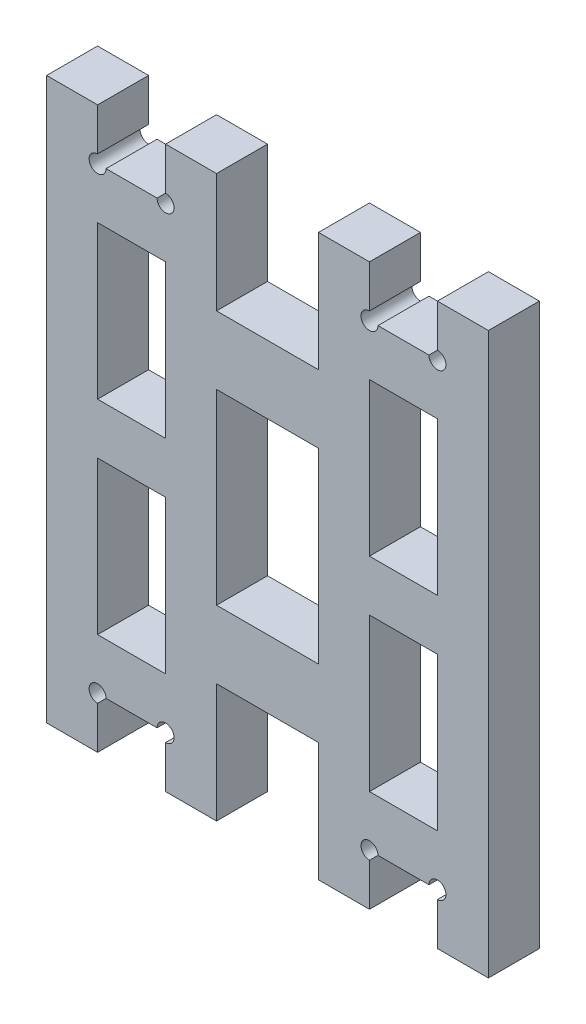
SolidWorks part; units mm, degrees
ref_plane "前视基准面" through (0, 0, 0) normal (0, 0, 1) x (1, 0, 0)
ref_plane "上视基准面" through (0, 0, 0) normal (0, 1, 0) x (1, 0, 0)
ref_plane "右视基准面" through (0, 0, 0) normal (1, 0, 0) x (0, 0, -1)
sketch "草图1" plane through (0, 0, 0) normal (0, 0, 1) x (1, 0, 0)
  line L0 (10, 26) -> (10, 33)
  line L1 (16, 26) -> (10, 26)
  line L2 (16, 22) -> (10, 22)
  line L3 (16, 33) -> (16, 26)
  line L4 (19, 33) -> (16, 33)
  line L5 (19, 30.5) -> (19, 33)
  line L6 (22.5, 30) -> (19.5, 30)
  line L7 (23, 33) -> (23, 30.5)
  line L8 (26, 33) -> (23, 33)
  line L9 (26, 0) -> (26, 33)
  line L10 (23, 0) -> (26, 0)
  line L11 (23, 2.5) -> (23, 0)
  line L12 (19.5, 3) -> (22.5, 3)
  line L13 (19, 0) -> (19, 2.5)
  line L14 (16, 0) -> (19, 0)
  line L15 (16, 7) -> (16, 0)
  line L16 (10, 0) -> (10, 7)
  line L17 (7, 0) -> (10, 0)
  line L18 (7, 2.5) -> (7, 0)
  line L19 (3.5, 3) -> (6.5, 3)
  line L20 (3, 0) -> (3, 2.5)
  line L21 (0, 0) -> (3, 0)
  line L22 (0, 33) -> (0, 0)
  line L23 (3, 33) -> (0, 33)
  line L24 (3, 30.5) -> (3, 33)
  line L25 (6.5, 30) -> (3.5, 30)
  line L26 (7, 33) -> (7, 30.5)
  line L27 (10, 33) -> (7, 33)
  line L28 (16, 7) -> (10, 7)
  line L29 (7, 18) -> (7, 27)
  line L30 (10, 11) -> (10, 22)
  line L31 (7, 27) -> (3, 27)
  line L32 (3, 27) -> (3, 18)
  line L33 (3, 18) -> (7, 18)
  line L34 (7, 6) -> (7, 15)
  line L35 (7, 15) -> (3, 15)
  line L36 (3, 15) -> (3, 6)
  line L37 (3, 6) -> (7, 6)
  line L38 (19, 15) -> (19, 6)
  line L39 (19, 6) -> (23, 6)
  line L40 (23, 6) -> (23, 15)
  line L41 (23, 15) -> (19, 15)
  line L42 (23, 18) -> (23, 27)
  line L43 (23, 27) -> (19, 27)
  line L44 (19, 27) -> (19, 18)
  line L45 (16, 22) -> (16, 11)
  line L46 (19, 18) -> (23, 18)
  line L47 (16, 11) -> (10, 11)
  arc A0 (19, 30.5) -> (19.5, 30) centre (19, 30) ccw
  arc A1 (22.5, 30) -> (23, 30.5) centre (23, 30) ccw
  arc A2 (23, 2.5) -> (22.5, 3) centre (23, 3) ccw
  arc A3 (19.5, 3) -> (19, 2.5) centre (19, 3) ccw
  arc A4 (7, 2.5) -> (6.5, 3) centre (7, 3) ccw
  arc A5 (3.5, 3) -> (3, 2.5) centre (3, 3) ccw
  arc A6 (3, 30.5) -> (3.5, 30) centre (3, 30) ccw
  arc A7 (6.5, 30) -> (7, 30.5) centre (7, 30) ccw
extrude "凸台-拉伸1" add sketch "草图1" along normal blind 3
